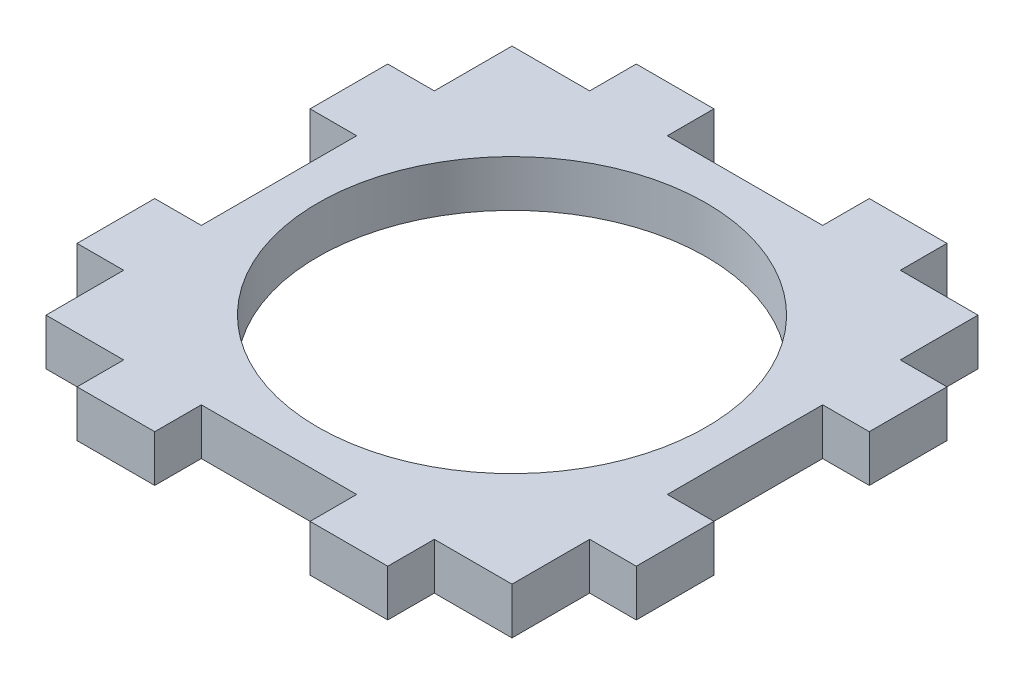
SolidWorks part; units mm, degrees
ref_plane "Front Plane" through (0, 0, 0) normal (0, 0, 1) x (1, 0, 0)
ref_plane "Top Plane" through (0, 0, 0) normal (0, 1, 0) x (1, 0, 0)
ref_plane "Right Plane" through (0, 0, 0) normal (1, 0, 0) x (0, 0, -1)
sketch "Sketch1" plane through (0, 0, 0) normal (0, 1, 0) x (1, 0, 0)
  line L0 (2.2355, 32.0745) -> (0, 30) construction
  line L1 (-30, 30) -> (30, 30)
  line L2 (-30, 30) -> (-30, -30)
  line L3 (-30, -30) -> (30, -30)
  line L4 (30, 30) -> (30, -30)
  line L5 (-30, 30) -> (30, -30) construction
  line L6 (-30, -30) -> (30, 30) construction
  line L7 (0, 30) -> (0, -30) construction
  line L8 (-30, 0) -> (30, 0) construction
  line L9 (10, -30) -> (10, -36)
  line L10 (-20, -30) -> (-10, -30)
  line L11 (-20, -30) -> (-20, -36)
  line L12 (-20, -36) -> (-10, -36)
  line L13 (-10, -30) -> (-10, -36)
  line L14 (20, -36) -> (10, -36)
  line L15 (20, -30) -> (20, -36)
  line L16 (20, -30) -> (10, -30)
  line L17 (-30, -10) -> (-36, -10)
  line L18 (-30, 20) -> (-30, 10)
  line L19 (-30, 20) -> (-36, 20)
  line L20 (-36, 20) -> (-36, 10)
  line L21 (-30, 10) -> (-36, 10)
  line L22 (-36, -20) -> (-36, -10)
  line L23 (-30, -20) -> (-36, -20)
  line L24 (-30, -20) -> (-30, -10)
  line L25 (-10, 30) -> (-10, 36)
  line L26 (20, 30) -> (10, 30)
  line L27 (20, 30) -> (20, 36)
  line L28 (20, 36) -> (10, 36)
  line L29 (10, 30) -> (10, 36)
  line L30 (-20, 36) -> (-10, 36)
  line L31 (-20, 30) -> (-20, 36)
  line L32 (-20, 30) -> (-10, 30)
  line L33 (30, 10) -> (36, 10)
  line L34 (30, -20) -> (30, -10)
  line L35 (30, -20) -> (36, -20)
  line L36 (36, -20) -> (36, -10)
  line L37 (30, -10) -> (36, -10)
  line L38 (36, 20) -> (36, 10)
  line L39 (30, 20) -> (36, 20)
  line L40 (30, 20) -> (30, 10)
  circle A0 centre (0, 0) radius 25
  point P0 (0, 0)
  point P46 (0, 0)
  dimension "D7" = 50
  dimension "D1" = 60
  dimension "D2" = 60
  dimension "D3" = 10
  dimension "D4" = 10
  dimension "D5" = 4
  dimension "D6" = 6
extrude "Boss-Extrude1" add sketch "Sketch1" along normal blind 6 contours L4 L1 L2 L3 | L15 L3 L9 L14 | L13 L3 L11 L12 | L37 L4 L35 L36 | L39 L4 L33 L38 | L23 L2 L17 L22 | L21 L2 L19 L20 | L31 L1 L25 L30 | L29 L1 L27 L28
